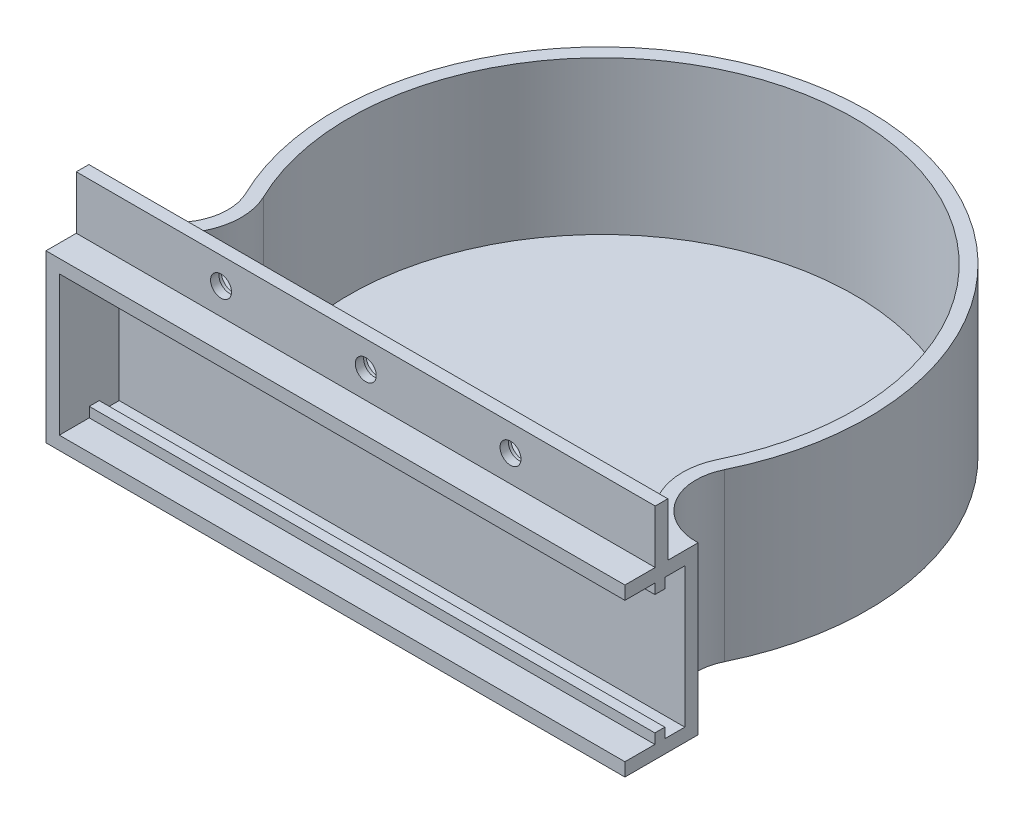
SolidWorks part; units mm, degrees
ref_plane "Front Plane" through (0, 0, 0) normal (0, 0, 1) x (1, 0, 0)
ref_plane "Top Plane" through (0, 0, 0) normal (0, 1, 0) x (1, 0, 0)
ref_plane "Right Plane" through (0, 0, 0) normal (1, 0, 0) x (0, 0, -1)
sketch "Sketch1" plane through (0, 0, 0) normal (0, 0, 1) x (1, 0, 0)
  line L0 (-65.8813, 16.6687) -> (65.8812, 16.6687)
  line L1 (-65.0875, -15.875) -> (65.0875, -15.875) construction
  line L2 (-65.0875, -15.875) -> (-65.0875, 15.875) construction
  line L3 (-65.0875, 15.875) -> (65.0875, 15.875) construction
  line L4 (65.0875, -15.875) -> (65.0875, 15.875) construction
  line L5 (-65.0875, -15.875) -> (65.0875, 15.875) construction
  line L6 (-65.0875, 15.875) -> (65.0875, -15.875) construction
  line L7 (65.8812, -16.6688) -> (65.8812, 16.6687)
  line L8 (-65.8813, -16.6688) -> (65.8812, -16.6688)
  line L9 (-65.8813, -16.6688) -> (-65.8813, 16.6687)
  line L10 (-69.0563, 19.8437) -> (69.0562, 19.8438)
  line L11 (69.0562, -19.8438) -> (69.0562, 19.8438)
  line L12 (-69.0563, -19.8438) -> (69.0562, -19.8438)
  line L13 (-69.0563, -19.8438) -> (-69.0563, 19.8437)
  point P0 (0, 0)
  dimension "D1" = 130.175
  dimension "D2" = 31.75
  dimension "D3" = 0.7937
  dimension "D4" = 3.175
extrude "Boss-Extrude1" add sketch "Sketch1" along normal blind 14.2875
sketch "Sketch2" plane through (0, 0, 0) normal (0, 0, -1) x (-1, 0, 0)
  line L4 (69.0563, -19.8438) -> (69.0563, 19.8437)
  line L5 (69.0563, 19.8437) -> (-69.0562, 19.8438)
  line L6 (-69.0562, 19.8438) -> (-69.0562, -19.8438)
  line L7 (-69.0562, -19.8438) -> (69.0563, -19.8438)
  line L8 (69.0563, -19.8438) -> (69.0563, 19.8437)
  line L9 (69.0563, 19.8437) -> (-69.0562, 19.8438)
  line L10 (-69.0562, 19.8438) -> (-69.0562, -19.8438)
  line L11 (-69.0562, -19.8438) -> (69.0563, -19.8438)
  dimension "D1" = 0
extrude "Boss-Extrude2" add sketch "Sketch2" along normal blind 3.175
sketch "Sketch3" plane through (69.0562, 0, 0) normal (1, 0, 0) x (0, 0, -1)
  line L4 (0, -16.6687) -> (0, 16.6688)
  line L5 (0, 16.6688) -> (-14.2875, 16.6688)
  line L6 (-14.2875, 16.6688) -> (-14.2875, -16.6687)
  line L7 (-14.2875, -16.6687) -> (0, -16.6687)
  line L8 (0, -16.6687) -> (0, 16.6688)
  line L9 (0, 16.6688) -> (-14.2875, 16.6688)
  line L10 (-14.2875, 16.6688) -> (-14.2875, -16.6687)
  line L11 (-14.2875, -16.6687) -> (0, -16.6687)
  dimension "D1" = 0
extrude "Cut-Extrude1" cut sketch "Sketch3" against normal up to next
sketch "Sketch4" plane through (69.0562, 0, 0) normal (1, 0, 0) x (0, 0, -1)
  line L0 (-14.2875, -16.6687) -> (0, -16.6687) construction
  line L1 (-7.1437, -16.6687) -> (-4.7625, -16.6687)
  line L2 (-7.1437, -16.6687) -> (-7.1437, -14.2875)
  line L3 (-7.1437, -14.2875) -> (-4.7625, -14.2875)
  line L4 (-4.7625, -16.6687) -> (-4.7625, -14.2875)
  line L5 (0, 16.6688) -> (-14.2875, 16.6688) construction
  line L6 (-7.1437, 16.6688) -> (-4.7625, 16.6688)
  line L7 (-7.1437, 16.6688) -> (-7.1437, 14.2875)
  line L8 (-7.1437, 14.2875) -> (-4.7625, 14.2875)
  line L9 (-4.7625, 16.6688) -> (-4.7625, 14.2875)
  line L10 (-14.2875, -19.8438) -> (-14.2875, -16.6687) construction
  dimension "D1" = 7.1437
  dimension "D2" = 2.3812
  dimension "D3" = 2.3812
extrude "Boss-Extrude3" add sketch "Sketch4" against normal up to next
sketch "Sketch6" plane through (0, 0, -3.175) normal (0, 0, -1) x (-1, 0, 0)
  line L0 (69.0563, -19.8438) -> (69.0563, 19.8437) construction
  line L1 (-69.0562, 19.8438) -> (69.0563, 19.8438)
  line L2 (-69.0562, 19.8438) -> (-69.0562, 32.5437)
  line L3 (-69.0562, 32.5437) -> (69.0563, 32.5437)
  line L4 (69.0563, 19.8438) -> (69.0563, 32.5437)
  line L5 (-34.5281, 26.1937) -> (0, 26.1937) construction
  line L6 (0, 26.1937) -> (34.5281, 26.1937) construction
  line L7 (34.5281, 26.1937) -> (69.0563, 26.1937) construction
  circle A0 centre (0, 26.1937) radius 2.5
  circle A1 centre (-34.5281, 26.1937) radius 2.5
  circle A2 centre (34.5281, 26.1937) radius 2.5
  point P13 (0, 0)
  point P14 (-69.0562, 26.1937)
  dimension "D2" = 5
  dimension "D1" = 12.7
extrude "Boss-Extrude4" add sketch "Sketch6" along normal mid plane 3 from offset 8.7312 offset against normal yes
sketch "Sketch7" plane through (0, 0, 4.0563) normal (0, 0, -1) x (-1, 0, 0)
  circle A0 centre (-34.5281, 26.1937) radius 2.95
  circle A1 centre (0, 26.1937) radius 2.95
  circle A2 centre (34.5281, 26.1937) radius 2.95
  dimension "D1" = 5.9
extrude "Cut-Extrude2" cut sketch "Sketch7" against normal blind 1
sketch "Sketch8" plane through (0, -19.8438, 0) normal (0, -1, 0) x (1, 0, 0)
  line L0 (69.0562, -3.175) -> (-69.0563, -3.175) construction
  line L1 (-69.0563, 14.2875) -> (69.0562, 14.2875) construction
  circle A0 centre (0, -49.2125) radius 63.5
  point P2 (0, 0)
  point P5 (0, -3.175)
  dimension "D1" = 127
extrude "Boss-Extrude5" add sketch "Sketch8" against normal up to surface (3.175 mm away) up to face at (1.5875, -16.6687, 10.7156)
fillet "Fillet1" radius 12.7 2 edges at (43.7356, -18.2563, -3.175) (-43.7356, -18.2563, -3.175)
sketch "Sketch10" plane through (0, -16.6688, 0) normal (0, 1, 0) x (1, 0, 0)
  line L0 (-68.5204, 3.175) -> (68.5204, 3.175) construction
  line L1 (-68.5204, 3.175) -> (-58.9954, 3.175)
  line L2 (58.9954, 3.175) -> (68.5204, 3.175)
  arc A0 (-68.5204, 3.175) -> (-57.1004, 21.4313) centre (-68.5204, 15.875) ccw construction
  arc A1 (57.1004, 21.4313) -> (-57.1004, 21.4313) centre (0, 49.2125) ccw construction
  arc A2 (57.1004, 21.4313) -> (68.5204, 3.175) centre (68.5204, 15.875) ccw construction
  arc A3 (-68.5204, 3.175) -> (-57.1004, 21.4313) centre (-68.5204, 15.875) ccw
  arc A4 (57.1004, 21.4313) -> (-57.1004, 21.4313) centre (0, 49.2125) ccw
  arc A5 (57.1004, 21.4313) -> (68.5204, 3.175) centre (68.5204, 15.875) ccw
  arc A6 (-58.9954, 3.175) -> (-54.2454, 22.8203) centre (-68.5204, 15.875) ccw
  arc A7 (54.2454, 22.8203) -> (-54.2454, 22.8203) centre (0, 49.2125) ccw
  arc A8 (54.2454, 22.8203) -> (58.9954, 3.175) centre (68.5204, 15.875) ccw
  arc A9 (54.2454, 22.8203) -> (68.5204, 0) centre (68.5204, 15.875) ccw construction
  arc A10 (-68.5204, 0) -> (-54.2454, 22.8203) centre (-68.5204, 15.875) ccw construction
  dimension "D1" = 3.175
extrude "Boss-Extrude6" add sketch "Sketch10" along normal up to surface (36.5125 mm away) up to face at (0, 19.8438, 0.4406)
